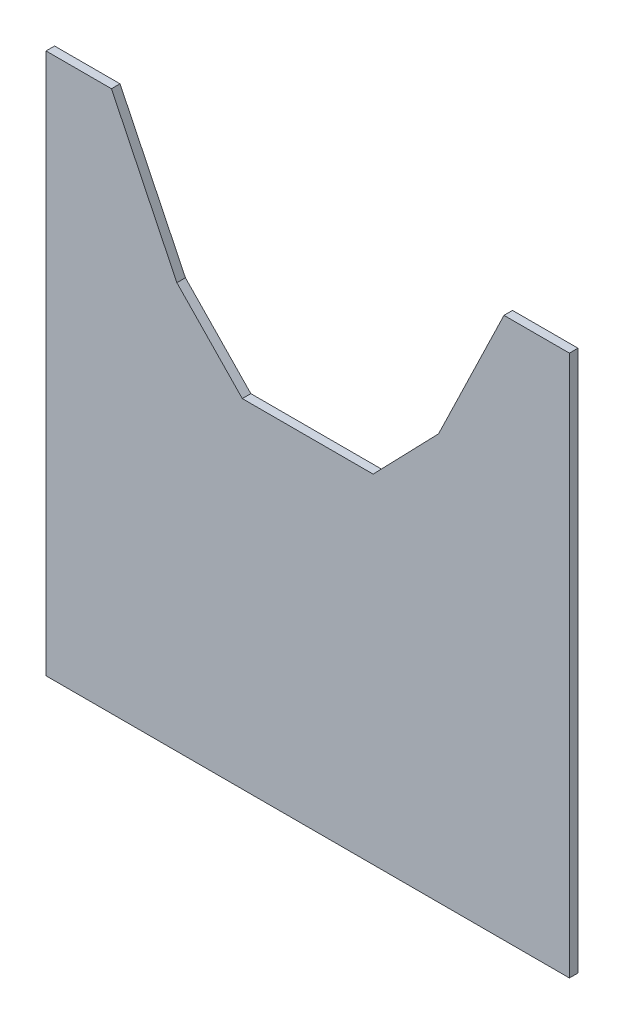
SolidWorks part; units mm, degrees
ref_plane "Front Plane" through (0, 0, 0) normal (0, 0, 1) x (1, 0, 0)
ref_plane "Top Plane" through (0, 0, 0) normal (0, 1, 0) x (1, 0, 0)
ref_plane "Right Plane" through (0, 0, 0) normal (1, 0, 0) x (0, 0, -1)
sketch "Sketch1" plane through (0, 0, 0) normal (0, 0, 1) x (1, 0, 0)
  line L0 (0, -100.457) -> (0, 0) construction
  line L1 (-97.155, 100.457) -> (-72.8663, 100.457)
  line L2 (-97.155, 100.457) -> (-97.155, -100.457)
  line L3 (-97.155, -100.457) -> (97.155, -100.457)
  line L4 (97.155, 100.457) -> (97.155, -100.457)
  line L5 (0, 0) -> (-97.155, 0) construction
  line L6 (-97.155, 100.457) -> (-97.155, 0) construction
  line L7 (-48.5775, 0) -> (-48.5775, 100.457) construction
  line L8 (-48.5775, 50.2285) -> (-97.155, 50.2285) construction
  line L9 (-72.8662, 50.2285) -> (-72.8663, 100.457) construction
  line L10 (-72.8663, 100.457) -> (-48.5775, 50.2285) construction
  line L11 (0, 0) -> (97.155, 0) construction
  line L12 (48.5775, 0) -> (48.5775, 100.457) construction
  line L13 (0, 0) -> (-48.5775, 50.2285) construction
  line L14 (-24.2887, 25.1142) -> (0, 25.1142) construction
  line L15 (-72.8663, 100.457) -> (-48.5775, 50.2285)
  line L16 (-48.5775, 50.2285) -> (-24.2887, 25.1142)
  line L17 (-24.2887, 25.1142) -> (24.2887, 25.1142)
  line L18 (72.8663, 100.457) -> (97.155, 100.457)
  line L19 (48.5775, 50.2285) -> (24.2887, 25.1142)
  line L20 (72.8663, 100.457) -> (48.5775, 50.2285)
  line L21 (-72.8663, 100.457) -> (72.8663, 100.457) construction
  point P0 (0, 0)
  point P23 (0, 0)
  dimension "D1" = 194.31
  dimension "D2" = 200.914
extrude "Boss-Extrude1" add sketch "Sketch1" along normal blind 3.175 contours L1 L15 L16 L17 L19 L20 L18 L4 L3 L2
